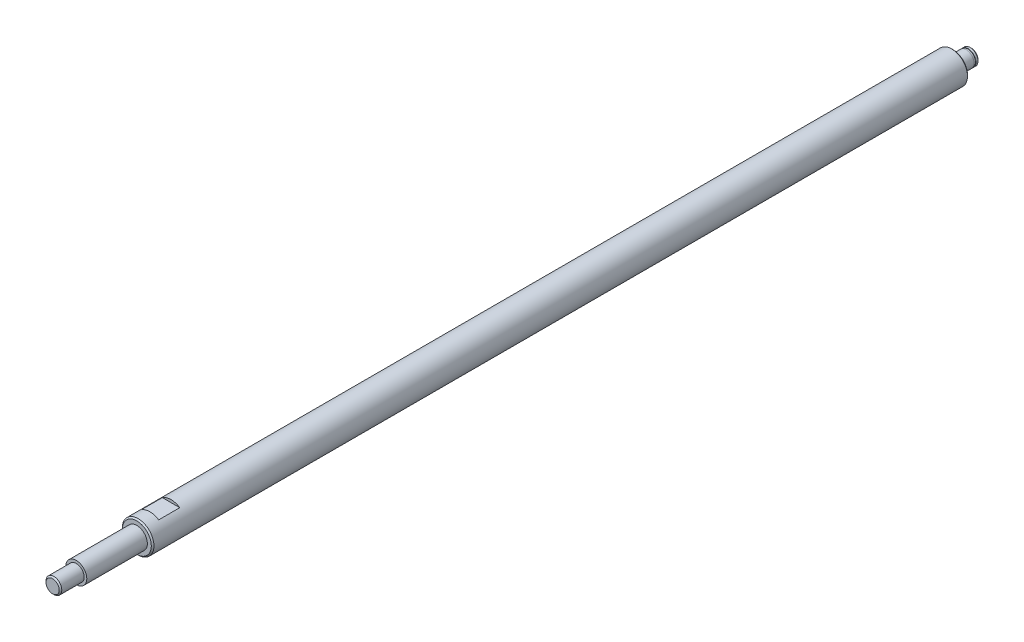
SolidWorks part; units mm, degrees
ref_plane "前视基准面" through (0, 0, 0) normal (0, 0, 1) x (1, 0, 0)
ref_plane "上视基准面" through (0, 0, 0) normal (0, 1, 0) x (1, 0, 0)
ref_plane "右视基准面" through (0, 0, 0) normal (1, 0, 0) x (0, 0, -1)
sketch "草图1" plane through (0, 0, 0) normal (0, 0, 1) x (1, 0, 0)
  circle A0 centre (0, 0) radius 6
  dimension "D1" = 12
extrude "凸台-拉伸1" add sketch "草图1" along normal mid plane 310
sketch "草图2" plane through (0, 0, -155) normal (0, 0, -1) x (-1, 0, 0)
  circle A0 centre (0, 0) radius 3
  dimension "D1" = 6
extrude "凸台-拉伸2" add sketch "草图2" along normal blind 7
sketch "草图3" plane through (0, 0, -155) normal (0, 0, -1) x (-1, 0, 0)
  circle A0 centre (0, 0) radius 2.85
  circle A1 centre (0, 0) radius 3 construction
  circle A2 centre (0, 0) radius 3
  dimension "D1" = 5.7
extrude "切除-拉伸1" cut sketch "草图3" along normal blind 0.7 from offset 5
sketch "草图4" plane through (0, 0, 155) normal (0, 0, 1) x (1, 0, 0)
  circle A0 centre (0, 0) radius 4
  dimension "D1" = 8
extrude "凸台-拉伸3" add sketch "草图4" along normal blind 23
cosmetic thread "装饰螺纹线1" parameters "D1"=10, "D2"=7.5
sketch "草图5" plane through (0, 0, 178) normal (0, 0, 1) x (1, 0, 0)
  circle A0 centre (0, 0) radius 3
  dimension "D1" = 6
extrude "凸台-拉伸4" add sketch "草图5" along normal blind 9
chamfer "倒角1" distance 0.5 angle 45 4 edges at (3, 0, 187) (6, 0, 155) (6, 0, -155) (-3, 0, -162)
ref_plane "基准面1" through (0, 6, 0) normal (0, 1, 0) x (1, 0, 0)
sketch "草图6" plane through (0, 6, 0) normal (0, 1, 0) x (1, 0, 0)
  line L0 (-4, -155) -> (4, -155) construction
  line L1 (-4.6509, -142) -> (4.6509, -142)
  line L2 (-4.6509, -142) -> (-4.6509, -150)
  line L3 (-4.6509, -150) -> (4.6509, -150)
  line L4 (4.6509, -142) -> (4.6509, -150)
  line L5 (0, -155) -> (0, -181.694) construction
  dimension "D1" = 5
  dimension "D2" = 8
extrude "切除-拉伸2" cut sketch "草图6" against normal blind 1
mirror "镜向1" about plane through (0, 0, 0) normal (0, 1, 0) of "切除-拉伸2"
sketch "草图7" plane through (0, 0, 155) normal (0, 0, 1) x (1, 0, 0)
  circle A0 centre (0, 0) radius 6.75
  dimension "D1" = 13.5
sketch "草图8" plane through (0, 0, 187) normal (0, 0, 1) x (1, 0, 0)
  line L0 (0, 0) -> (0, 5) construction
  line L1 (-1.5, 4.3283) -> (1.5, 4.3283)
  line L2 (-1.5, 4.3283) -> (-1.5, 2.2)
  line L3 (-1.5, 2.2) -> (1.5, 2.2)
  line L4 (1.5, 4.3283) -> (1.5, 2.2)
  line L5 (3.3166, 5) -> (-3.3166, 5) construction
  dimension "D1" = 2.2
  dimension "D2" = 3
extrude "切除-拉伸3" [suppressed] cut sketch "草图8" against normal up to surface (9 mm away)
fillet "圆角1" [suppressed] radius 1.5
